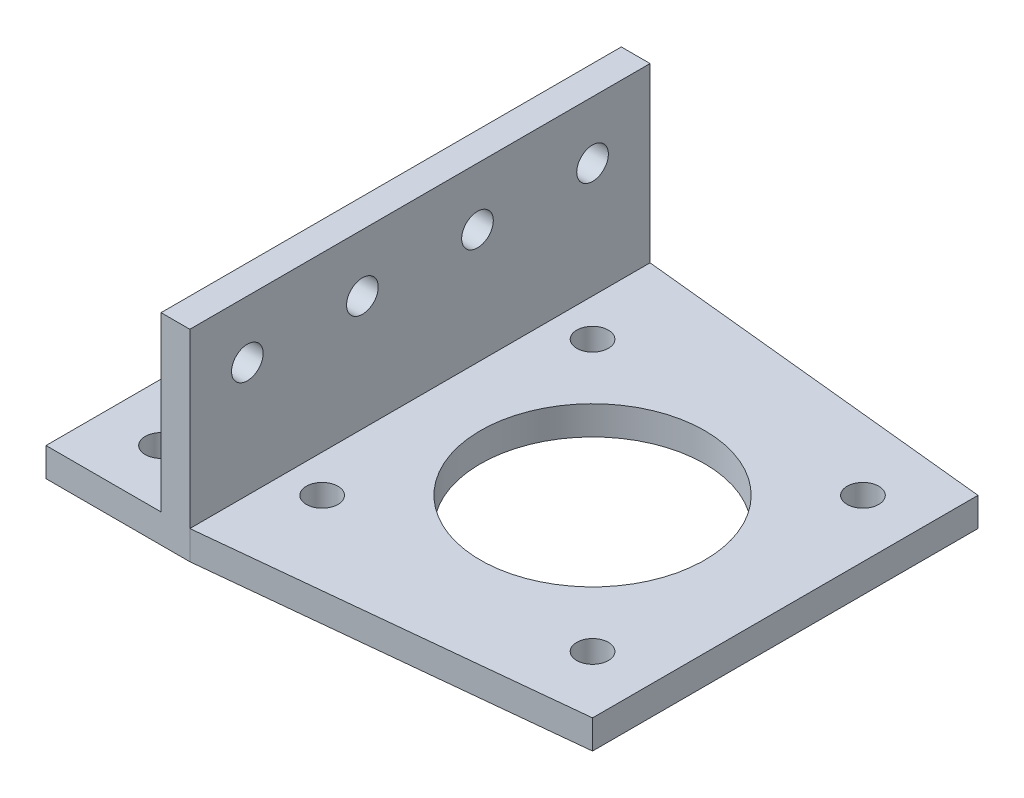
SolidWorks part; units mm, degrees
ref_plane "Plan de face" through (0, 0, 0) normal (0, 0, 1) x (1, 0, 0)
ref_plane "Plan de dessus" through (0, 0, 0) normal (0, 1, 0) x (1, 0, 0)
ref_plane "Plan de droite" through (0, 0, 0) normal (1, 0, 0) x (0, 0, -1)
sketch "Esquisse1" plane through (0, 0, 0) normal (0, 0, 1) x (1, 0, 0)
  line L0 (-4.6419, 0) -> (-4.6419, 35)
  line L1 (-4.6419, 35) -> (-9.6419, 35)
  line L2 (-9.6419, 35) -> (-9.6419, 5)
  line L3 (-9.6419, 5) -> (-29.6419, 5)
  line L4 (-29.6419, 5) -> (-29.6419, 0)
  line L5 (-29.6419, 0) -> (-4.6419, 0)
  dimension "D1" = 20
  dimension "D2" = 5
  dimension "D3" = 30
extrude "Boss.-Extru.1" add sketch "Esquisse1" along normal blind 80
sketch "Esquisse2" plane through (-9.6419, 0, 0) normal (-1, 0, 0) x (0, 0, 1)
  line L0 (0, 35) -> (0, 5) construction
  line L1 (80, 35) -> (80, 5) construction
  line L2 (80, 35) -> (0, 35) construction
  circle A0 centre (10, 25) radius 2.75
  circle A1 centre (50, 25) radius 2.75
  circle A2 centre (70, 25) radius 2.75
  circle A3 centre (30, 25) radius 2.75
  dimension "D1" = 10
  dimension "D5" = 5.5
  dimension "D2" = 10
  dimension "D3" = 20
  dimension "D4" = 20
  dimension "D6" = 10
extrude "Enlèv. mat.-Extru.1" cut sketch "Esquisse2" against normal up to next
sketch "Esquisse3" plane through (0, 5, 0) normal (0, 1, 0) x (1, 0, 0)
  line L0 (-9.6419, -7.25) -> (-9.6419, -12.75) construction
  line L1 (-9.6419, -27.25) -> (-9.6419, -32.75) construction
  line L2 (-9.6419, -47.25) -> (-9.6419, -52.75) construction
  line L3 (-9.6419, -67.25) -> (-9.6419, -72.75) construction
  line L4 (-9.6419, -7.25) -> (-9.6419, -12.75) construction
  line L5 (-9.6419, -27.25) -> (-9.6419, -32.75) construction
  line L6 (-9.6419, -47.25) -> (-9.6419, -52.75) construction
  line L7 (-9.6419, -67.25) -> (-9.6419, -72.75) construction
  line L8 (-9.6419, 0) -> (-29.6419, 0) construction
  circle A0 centre (-19.6419, -10) radius 2.75
  circle A1 centre (-19.6419, -30) radius 2.75
  circle A2 centre (-19.6419, -50) radius 2.75
  circle A3 centre (-19.6419, -70) radius 2.75
  point P17 (-9.6419, -70)
  point P19 (-9.6419, -50)
  point P21 (-9.6419, -30)
  point P23 (-9.6419, -10)
  point P27 (-19.6419, 0)
  dimension "D1" = 5.5
extrude "Enlèv. mat.-Extru.2" cut sketch "Esquisse3" against normal up to next
sketch "Esquisse5" plane through (0, 0, 0) normal (0, -1, 0) x (1, 0, 0)
  line L0 (58.8581, 73.5) -> (-4.6419, 80)
  line L1 (-4.6419, 0) -> (58.8581, 6.5)
  line L2 (-4.6419, 0) -> (-4.6419, 80)
  line L4 (58.8581, 6.5) -> (58.8581, 73.5)
  line L5 (48.8581, 16.5) -> (48.8581, 63.5) construction
  line L6 (48.8581, 16.5) -> (1.8581, 16.5) construction
  line L7 (48.8581, 16.5) -> (58.8581, 16.5) construction
  line L8 (48.8581, 16.5) -> (48.8581, 6.5) construction
  line L9 (48.8581, 63.5) -> (58.8581, 63.5) construction
  line L10 (48.8581, 63.5) -> (48.8581, 73.5) construction
  circle A0 centre (25.3581, 40) radius 19.5
  circle A1 centre (48.8581, 16.5) radius 2.75
  circle A2 centre (48.8581, 63.5) radius 2.75
  circle A3 centre (1.8581, 63.5) radius 2.75
  circle A4 centre (1.8581, 16.5) radius 2.75
  point P16 (48.8581, 40)
  point P18 (25.3581, 16.5)
  point P24 (-4.6419, 40)
  line M6 (-4.6419, 0) -> (-4.6419, 80)
  dimension "D3" = 39
  dimension "D4" = 5.5
  dimension "D1" = 30
  dimension "D2" = 10
  dimension "D5" = 47
extrude "Boss.-Extru.2" add sketch "Esquisse5" against normal blind 5 contours A4 L1 L4 L0 A3 A2 A1 A0 M6
